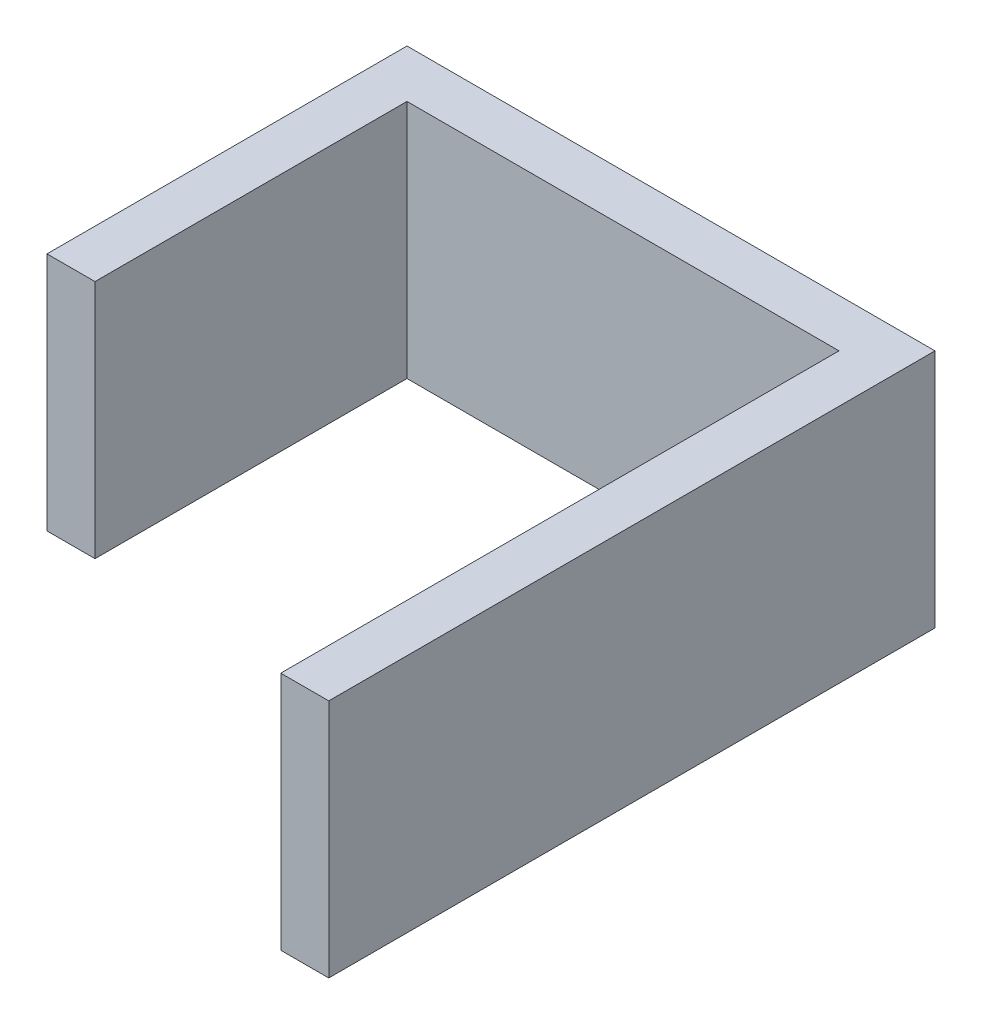
SolidWorks part; units mm, degrees
ref_plane "前基準面" through (0, 0, 0) normal (0, 0, 1) x (1, 0, 0)
ref_plane "上基準面" through (0, 0, 0) normal (0, 1, 0) x (1, 0, 0)
ref_plane "右基準面" through (0, 0, 0) normal (1, 0, 0) x (0, 0, -1)
sketch "草圖1" plane through (0, 0, 0) normal (0, 1, 0) x (1, 0, 0)
  line L0 (-10, -7.5) -> (-8, -7.5)
  line L3 (10, 7.5) -> (-10, 7.5)
  line L4 (-10, -7.5) -> (-10, 7.5)
  line L5 (-8, 5.5) -> (10, 5.5)
  line L6 (-8, 5.5) -> (-8, -7.5)
  line L8 (10, 5.5) -> (10, -17.7602)
  line L9 (12, -17.7602) -> (12, 7.5)
  line L10 (10, -17.7602) -> (12, -17.7602)
  line L11 (10, 7.5) -> (12, 7.5)
  point P0 (0, 0)
  dimension "D2" = 20
  dimension "D3" = 2
  dimension "D5" = 2
extrude "填料-伸長1" add sketch "草圖1" along normal blind 10
